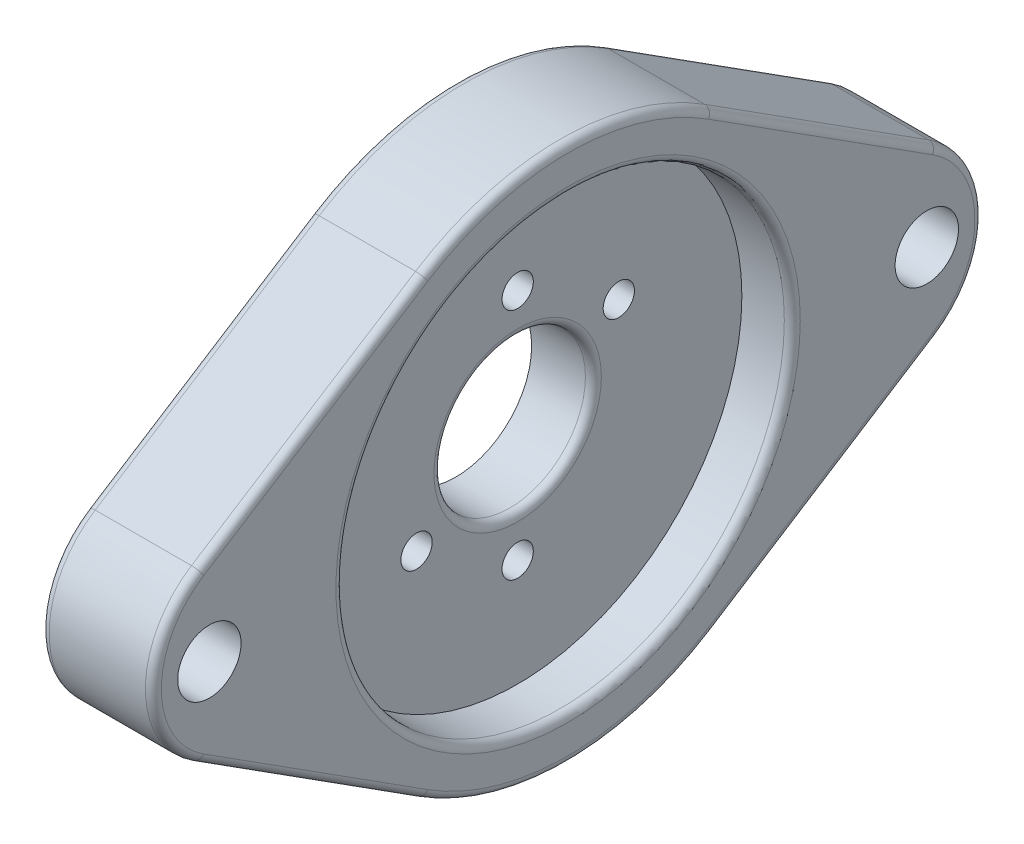
SolidWorks part; units mm, degrees
material "ABS"
ref_plane "Front Plane" through (0, 0, 0) normal (0, 0, 1) x (1, 0, 0)
ref_plane "Top Plane" through (0, 0, 0) normal (0, 1, 0) x (1, 0, 0)
ref_plane "Right Plane" through (0, 0, 0) normal (1, 0, 0) x (0, 0, -1)
sketch "Sketch1" plane through (0, 0, 0) normal (1, 0, 0) x (0, 0, -1)
  line L6 (9.2165, 14.4571) -> (23.495, 5.3545)
  line L9 (-9.2165, 14.4571) -> (-23.495, 5.3545)
  line L13 (-23.495, -5.3545) -> (-9.2165, -14.4571)
  line L14 (23.495, -5.3545) -> (9.2165, -14.4571)
  line L21 (23.495, 5.3545) -> (23.495, -5.3545) construction
  line L22 (-20.0815, 0) -> (20.0815, 0) construction
  line L23 (23.495, -5.3545) -> (-23.495, -5.3545) construction
  line L24 (-23.495, -5.3545) -> (-23.495, 5.3545) construction
  line L25 (23.495, 5.3545) -> (-23.495, 5.3545) construction
  arc A6 (23.495, 5.3545) -> (23.495, -5.3545) centre (20.0815, 0) cw
  arc A7 (-23.495, 5.3545) -> (-23.495, -5.3545) centre (-20.0815, 0) ccw
  arc A8 (-9.2165, -14.4571) -> (9.2165, -14.4571) centre (0, 0) ccw
  arc A9 (9.2165, 14.4571) -> (-9.2165, 14.4571) centre (0, 0) ccw
  dimension "D1" = 17.145
  dimension "D2" = 46.99
  dimension "D3" = 6.35
extrude "Boss-Extrude3" add sketch "Sketch1" along normal blind 7.1501
sketch "Sketch5" plane through (7.1501, 0, 0) normal (1, 0, 0) x (0, 0, -1)
  circle A0 centre (0, 0) radius 4.826
  dimension "D1" = 9.652
extrude "Cut-Extrude4" cut sketch "Sketch5" against normal through all
sketch "Sketch6" plane through (7.1501, 0, 0) normal (1, 0, 0) x (0, 0, -1)
  circle A0 centre (0, 0) radius 14.2875
  dimension "D1" = 28.575
extrude "Cut-Extrude5" cut sketch "Sketch6" against normal blind 3.2131
hole_wizard "Tap Drill for #3-48 Tap2" positions "Sketch10" profile "Sketch11" hole size "#3-48" standard "ANSI Inch" end condition through all
sketch "Sketch10" plane through (3.937, 0, 0) normal (1, 0, 0) x (0, 0, -1)
  line L0 (0, -7.4422) -> (0, 7.4422) construction
  line L1 (6.4451, 3.7211) -> (-6.4451, -3.7211) construction
  point P0 (0, 7.4422)
  point P2 (0, -7.4422)
  point P14 (6.4451, 3.7211)
  point P17 (-6.4451, -3.7211)
  dimension "D1" = 14.8844
  dimension "D2" = 60
sketch "Sketch11" plane through (3.937, 7.4422, 0) normal (0, 1, 0) x (0, 0, -1)
  line L0 (0, 0) -> (0, 3.937)
  line L1 (0, 3.937) -> (0.9969, 3.937)
  line L2 (0.9969, 3.937) -> (0.9969, 0)
  line L5 (0.9969, 0) -> (0, 0)
  line L11 (0, -6.35) -> (0, 107.95) construction
  dimension "Thru Hole Dia." = 1.9939
  dimension "Thru Hole Depth" = 3.937
hole_wizard "Tap Drill for #10-32 Tap3" positions "Sketch16" profile "Sketch17" hole size "#10-32" standard "ANSI Inch" end condition through all
sketch "Sketch16" plane through (7.1501, 0, 0) normal (1, 0, 0) x (0, 0, -1)
  line L4 (-22.86, 0) -> (22.86, 0) construction
  point P0 (-22.86, 0)
  point P2 (22.86, 0)
  dimension "D1" = 45.72
sketch "Sketch17" plane through (7.1501, 0, 22.86) normal (0, 1, 0) x (0, 0, -1)
  line L0 (0, 0) -> (0, 7.1501)
  line L1 (0, 7.1501) -> (2.0193, 7.1501)
  line L2 (2.0193, 7.1501) -> (2.0193, 0)
  line L5 (2.0193, 0) -> (0, 0)
  line L11 (0, -6.35) -> (0, 107.95) construction
  dimension "Thru Hole Dia." = 4.0386
  dimension "Thru Hole Depth" = 7.1501
fillet "Fillet3" radius 0.508 1 edges at (7.1501, 0, -14.2875)
fillet "Fillet4" radius 0.508 1 edges at (3.937, 0, -4.826)
fillet "Fillet5" radius 0.508 8 edges at (7.1501, 9.9058, -16.3557) (7.1501, 0, -26.4315) (7.1501, -9.9058, -16.3557) (7.1501, -17.145, 0) (7.1501, -9.9058, 16.3557) (7.1501, 0, 26.4315) (7.1501, 9.9058, 16.3557) (7.1501, 17.145, 0)
fillet "Fillet6" radius 0.508 8 edges at (0, 0, -26.4315) (0, -9.9058, -16.3557) (0, -17.145, 0) (0, -9.9058, 16.3557) (0, 0, 26.4315) (0, 9.9058, 16.3557) (0, 17.145, 0) (0, 9.9058, -16.3557)
